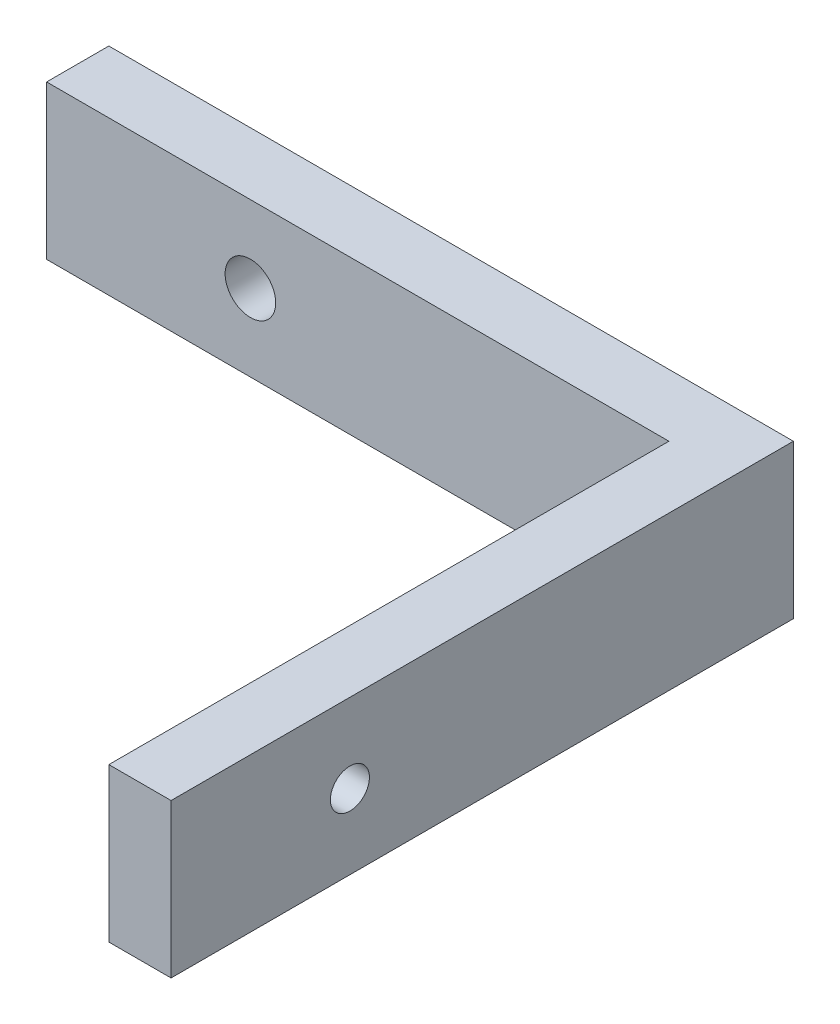
SolidWorks part; units mm, degrees
material "7075-T6 (SN)"
ref_plane "前视基准面" through (0, 0, 0) normal (0, 0, 1) x (1, 0, 0)
ref_plane "上视基准面" through (0, 0, 0) normal (0, 1, 0) x (1, 0, 0)
ref_plane "右视基准面" through (0, 0, 0) normal (1, 0, 0) x (0, 0, -1)
sketch "草图1" plane through (0, 0, 0) normal (0, 0, 1) x (1, 0, 0)
  line L0 (1.3394, 15.7386) -> (396.8937, 15.7386)
  line L2 (7.1415, 63.0878) -> (72.6396, 63.0878)
  line L3 (7.1415, 63.0878) -> (7.1415, 38.3894)
  line L4 (7.1415, 38.3894) -> (72.6396, 38.3894)
  line L5 (72.6396, 63.0878) -> (72.6396, 38.3894)
  line L6 (7.1415, 63.0878) -> (72.6396, 38.3894) construction
  line L7 (7.1415, 38.3894) -> (72.6396, 63.0878) construction
  circle A0 centre (39.8906, 15.7386) radius 35
  circle A1 centre (39.8906, 50.7386) radius 35
  circle A2 centre (39.8906, 50.7386) radius 4.0654
  dimension "D1" = 70
extrude "凸台-拉伸1" add sketch "草图1" against normal blind 10 contours A2 A0 L4 | A2 A0 L4 L5 L2 L3
sketch "草图2" plane through (0, 0, -10) normal (0, 0, -1) x (-1, 0, 0)
  line L0 (-72.6396, 63.0878) -> (-72.6396, 38.3894) construction
  line L1 (-72.6396, 63.0878) -> (-107.1415, 63.0878)
  line L2 (-72.6396, 63.0878) -> (-72.6396, 38.3894)
  line L3 (-72.6396, 38.3894) -> (-107.1415, 38.3894)
  line L4 (-107.1415, 63.0878) -> (-107.1415, 38.3894)
  line L5 (-7.1415, 63.0878) -> (-7.1415, 38.3894) construction
  dimension "D1" = 100
extrude "凸台-拉伸2" add sketch "草图2" against normal blind 10
sketch "草图3" plane through (107.1415, 0, 0) normal (1, 0, 0) x (0, 0, -1)
  line L0 (10, 63.0878) -> (10, 38.3894) construction
  line L1 (10, 63.0878) -> (-90, 63.0878)
  line L2 (10, 63.0878) -> (10, 38.3894)
  line L3 (10, 38.3894) -> (-90, 38.3894)
  line L4 (-90, 63.0878) -> (-90, 38.3894)
  circle A0 centre (-61.264, 50.3872) radius 3.1354
  dimension "D1" = 100
extrude "凸台-拉伸3" add sketch "草图3" along normal blind 10
